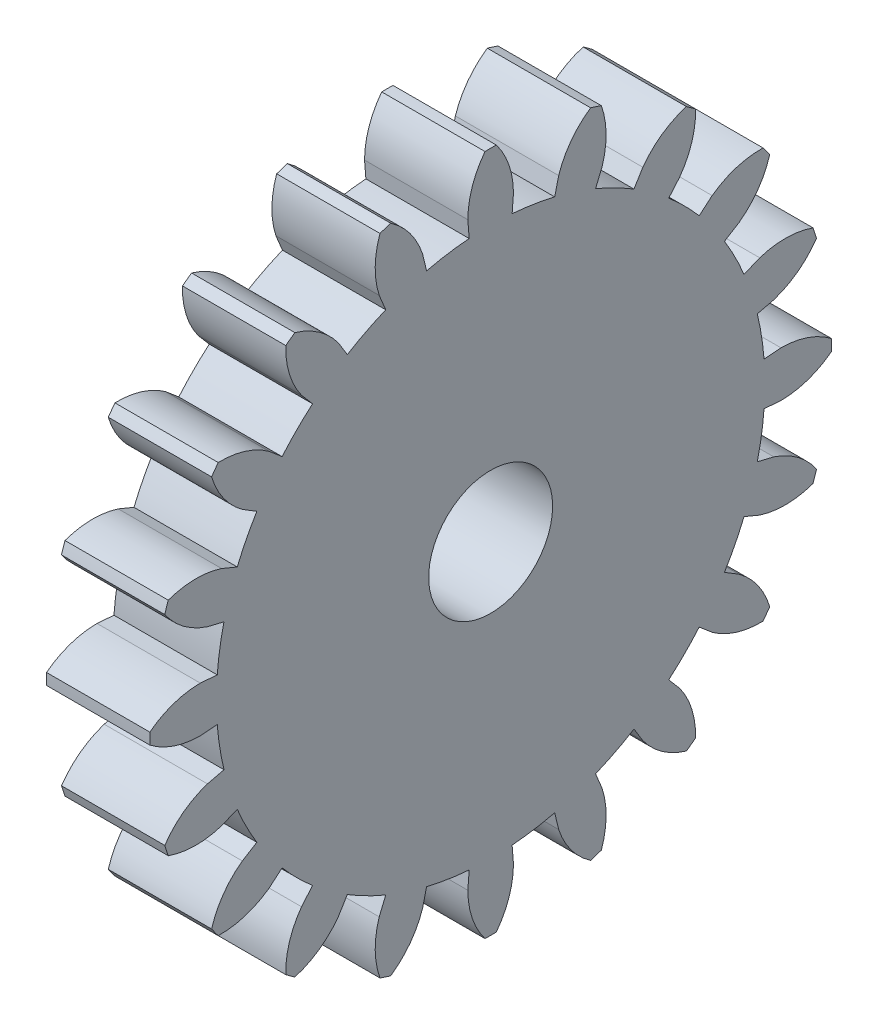
SolidWorks part; units mm, degrees
ref_plane "Front Plane" through (0, 0, 0) normal (1, 0, 0) x (0, 1, 0)
ref_plane "Top Plane" through (0, 0, 0) normal (0, 0, 1) x (0, 1, 0)
ref_plane "Right Plane" through (0, 0, 0) normal (0, 1, 0) x (-1, 0, 0)
sketch "Model" plane through (0, 0, 0) normal (1, 0, 0) x (0, 1, 0)
  line L0 (13.2342, -1.0397) -> (14.054, -1.1041)
  line L1 (14.054, 1.1041) -> (13.2342, 1.0397)
  line L2 (12.9078, 3.1007) -> (13.7073, 3.2929)
  line L3 (13.025, 5.3931) -> (12.2652, 5.0783)
  line L4 (11.3178, 6.9378) -> (12.0189, 7.3676)
  line L5 (10.7209, 9.1541) -> (10.0957, 8.6199)
  line L6 (8.6202, 10.0955) -> (9.1539, 10.7211)
  line L7 (7.3674, 12.0191) -> (6.9379, 11.3177)
  line L8 (5.0784, 12.2652) -> (5.3931, 13.0252)
  line L9 (3.293, 13.7076) -> (3.1008, 12.9078)
  line L10 (1.0397, 13.2342) -> (1.1041, 14.0542)
  line L11 (-1.1041, 14.0542) -> (-1.0397, 13.2342)
  line L12 (-3.1008, 12.9078) -> (-3.2929, 13.7076)
  line L13 (-5.3931, 13.0252) -> (-5.0784, 12.2652)
  line L14 (-6.9379, 11.3177) -> (-7.3679, 12.0191)
  line L15 (-9.1544, 10.7211) -> (-8.6202, 10.0955)
  line L16 (-10.0957, 8.6199) -> (-10.7214, 9.1541)
  line L17 (-12.0194, 7.3676) -> (-11.3178, 6.9378)
  line L18 (-12.2652, 5.0783) -> (-13.0255, 5.3931)
  line L19 (-13.7079, 3.2929) -> (-12.9078, 3.1007)
  line L20 (-13.2342, 1.0397) -> (-14.0545, 1.1041)
  line L21 (-14.0545, -1.1041) -> (-13.2342, -1.0397)
  line L22 (-12.9078, -3.1007) -> (-13.7079, -3.293)
  line L23 (-13.0255, -5.3931) -> (-12.2652, -5.0783)
  line L24 (-11.3178, -6.9378) -> (-12.0194, -7.3677)
  line L25 (-10.7214, -9.1542) -> (-10.0957, -8.6199)
  line L26 (-8.6202, -10.0955) -> (-9.1544, -10.7212)
  line L27 (-7.3679, -12.0191) -> (-6.9379, -11.3177)
  line L28 (-5.0784, -12.2652) -> (-5.3931, -13.0252)
  line L29 (-3.2929, -13.7076) -> (-3.1008, -12.9078)
  line L30 (-1.0397, -13.2342) -> (-1.1041, -14.0543)
  line L31 (1.1041, -14.0543) -> (1.0397, -13.2342)
  line L32 (3.1008, -12.9078) -> (3.293, -13.7076)
  line L33 (5.3931, -13.0252) -> (5.0784, -12.2652)
  line L34 (6.9379, -11.3177) -> (7.3674, -12.0191)
  line L35 (9.1539, -10.7212) -> (8.6202, -10.0955)
  line L36 (10.0957, -8.6199) -> (10.7209, -9.1542)
  line L37 (12.0189, -7.3677) -> (11.3178, -6.9378)
  line L38 (12.2652, -5.0783) -> (13.025, -5.3931)
  line L39 (13.7073, -3.293) -> (12.9078, -3.1007)
  circle A0 centre (0, 0) radius 3
  arc A1 (14.054, -1.1041) -> (16.4976, -0.2728) centre (14.0511, 2.9117) ccw
  arc A2 (16.4976, -0.2728) -> (16.4976, 0.2728) centre (0.0002, 0) ccw
  arc A3 (16.4976, 0.2728) -> (14.054, 1.1041) centre (14.0511, -2.9118) ccw
  arc A4 (13.2342, 1.0397) -> (12.9078, 3.1007) centre (0, 0) ccw
  arc A5 (13.7073, 3.2929) -> (15.7744, 4.8386) centre (12.4635, 7.1113) ccw
  arc A6 (15.7744, 4.8386) -> (15.6057, 5.3576) centre (0.0002, 0) ccw
  arc A7 (15.6057, 5.3576) -> (13.025, 5.3931) centre (14.2631, 1.5728) ccw
  arc A8 (12.2652, 5.0783) -> (11.3178, 6.9378) centre (0, 0) ccw
  arc A9 (12.0189, 7.3676) -> (13.5072, 9.4764) centre (9.656, 10.6148) ccw
  arc A10 (13.5072, 9.4764) -> (13.1865, 9.9179) centre (0.0002, 0.0026) ccw
  arc A11 (13.1865, 9.9179) -> (10.7209, 9.1541) centre (13.079, 5.9035) ccw
  arc A12 (10.0957, 8.6199) -> (8.6202, 10.0955) centre (0, 0) ccw
  arc A13 (9.1539, 10.7211) -> (9.9177, 13.1867) centre (5.9032, 13.0792) ccw
  arc A14 (9.9177, 13.1867) -> (9.4761, 13.5074) centre (0.002, 0.0005) ccw
  arc A15 (9.4761, 13.5074) -> (7.3674, 12.0191) centre (10.6146, 9.6562) ccw
  arc A16 (6.9379, 11.3177) -> (5.0784, 12.2652) centre (0, 0) ccw
  arc A17 (5.3931, 13.0252) -> (5.3577, 15.606) centre (1.5729, 14.2634) ccw
  arc A18 (5.3577, 15.606) -> (4.8386, 15.7747) centre (0, 0.0005) ccw
  arc A19 (4.8386, 15.7747) -> (3.293, 13.7076) centre (7.1114, 12.4638) ccw
  arc A20 (3.1008, 12.9078) -> (1.0397, 13.2342) centre (0, 0) ccw
  arc A21 (1.1041, 14.0542) -> (0.2728, 16.4979) centre (-2.9118, 14.0513) ccw
  arc A22 (0.2728, 16.4979) -> (-0.2728, 16.4979) centre (0, 0.0005) ccw
  arc A23 (-0.2728, 16.4979) -> (-1.1041, 14.0542) centre (2.9118, 14.0513) ccw
  arc A24 (-1.0397, 13.2342) -> (-3.1008, 12.9078) centre (0, 0) ccw
  arc A25 (-3.2929, 13.7076) -> (-4.8385, 15.7747) centre (-7.1113, 12.4638) ccw
  arc A26 (-4.8385, 15.7747) -> (-5.3576, 15.606) centre (0, 0.0005) ccw
  arc A27 (-5.3576, 15.606) -> (-5.3931, 13.0252) centre (-1.5728, 14.2634) ccw
  arc A28 (-5.0784, 12.2652) -> (-6.9379, 11.3177) centre (0, 0) ccw
  arc A29 (-7.3679, 12.0191) -> (-9.4768, 13.5074) centre (-10.6151, 9.6562) ccw
  arc A30 (-9.4768, 13.5074) -> (-9.9182, 13.1867) centre (0.0002, 0.0005) ccw
  arc A31 (-9.9182, 13.1867) -> (-9.1544, 10.7211) centre (-5.9038, 13.0792) ccw
  arc A32 (-8.6202, 10.0955) -> (-10.0957, 8.6199) centre (0, 0) ccw
  arc A33 (-10.7214, 9.1541) -> (-13.1869, 9.9179) centre (-13.0795, 5.9035) ccw
  arc A34 (-13.1869, 9.9179) -> (-13.5077, 9.4764) centre (-0.0007, -0.0006) ccw
  arc A35 (-13.5077, 9.4764) -> (-12.0194, 7.3676) centre (-9.6565, 10.6148) ccw
  arc A36 (-11.3178, 6.9378) -> (-12.2652, 5.0783) centre (0, 0) ccw
  arc A37 (-13.0255, 5.3931) -> (-15.6063, 5.3576) centre (-14.2636, 1.5728) ccw
  arc A38 (-15.6063, 5.3576) -> (-15.7749, 4.8386) centre (-0.0007, 0) ccw
  arc A39 (-15.7749, 4.8386) -> (-13.7079, 3.2929) centre (-12.4641, 7.1113) ccw
  arc A40 (-12.9078, 3.1007) -> (-13.2342, 1.0397) centre (0, 0) ccw
  arc A41 (-14.0545, 1.1041) -> (-16.4981, 0.2728) centre (-14.0516, -2.9118) ccw
  arc A42 (-16.4981, 0.2728) -> (-16.4981, -0.2728) centre (-0.0007, 0) ccw
  arc A43 (-16.4981, -0.2728) -> (-14.0545, -1.1041) centre (-14.0516, 2.9117) ccw
  arc A44 (-13.2342, -1.0397) -> (-12.9078, -3.1007) centre (0, 0) ccw
  arc A45 (-13.7079, -3.293) -> (-15.7749, -4.8386) centre (-12.4641, -7.1114) ccw
  arc A46 (-15.7749, -4.8386) -> (-15.6063, -5.3577) centre (-0.0007, 0) ccw
  arc A47 (-15.6063, -5.3577) -> (-13.0255, -5.3931) centre (-14.2636, -1.5729) ccw
  arc A48 (-12.2652, -5.0783) -> (-11.3178, -6.9378) centre (0, 0) ccw
  arc A49 (-12.0194, -7.3677) -> (-13.5077, -9.4765) centre (-9.6565, -10.6148) ccw
  arc A50 (-13.5077, -9.4765) -> (-13.1869, -9.918) centre (-0.0007, 0.0006) ccw
  arc A51 (-13.1869, -9.918) -> (-10.7214, -9.1542) centre (-13.0795, -5.9035) ccw
  arc A52 (-10.0957, -8.6199) -> (-8.6202, -10.0955) centre (0, 0) ccw
  arc A53 (-9.1544, -10.7212) -> (-9.9182, -13.1867) centre (-5.9038, -13.0793) ccw
  arc A54 (-9.9182, -13.1867) -> (-9.4768, -13.5075) centre (0.0002, -0.0005) ccw
  arc A55 (-9.4768, -13.5075) -> (-7.3679, -12.0191) centre (-10.6151, -9.6563) ccw
  arc A56 (-6.9379, -11.3177) -> (-5.0784, -12.2652) centre (0, 0) ccw
  arc A57 (-5.3931, -13.0252) -> (-5.3576, -15.606) centre (-1.5728, -14.2634) ccw
  arc A58 (-5.3576, -15.606) -> (-4.8385, -15.7747) centre (0, -0.0005) ccw
  arc A59 (-4.8385, -15.7747) -> (-3.2929, -13.7076) centre (-7.1113, -12.4638) ccw
  arc A60 (-3.1008, -12.9078) -> (-1.0397, -13.2342) centre (0, 0) ccw
  arc A61 (-1.1041, -14.0543) -> (-0.2728, -16.4979) centre (2.9118, -14.0513) ccw
  arc A62 (-0.2728, -16.4979) -> (0.2728, -16.4979) centre (0, -0.0005) ccw
  arc A63 (0.2728, -16.4979) -> (1.1041, -14.0543) centre (-2.9118, -14.0513) ccw
  arc A64 (1.0397, -13.2342) -> (3.1008, -12.9078) centre (0, 0) ccw
  arc A65 (3.293, -13.7076) -> (4.8386, -15.7747) centre (7.1114, -12.4638) ccw
  arc A66 (4.8386, -15.7747) -> (5.3577, -15.606) centre (0, -0.0005) ccw
  arc A67 (5.3577, -15.606) -> (5.3931, -13.0252) centre (1.5729, -14.2634) ccw
  arc A68 (5.0784, -12.2652) -> (6.9379, -11.3177) centre (0, 0) ccw
  arc A69 (7.3674, -12.0191) -> (9.4761, -13.5075) centre (10.6146, -9.6563) ccw
  arc A70 (9.4761, -13.5075) -> (9.9177, -13.1867) centre (0.002, -0.0005) ccw
  arc A71 (9.9177, -13.1867) -> (9.1539, -10.7212) centre (5.9032, -13.0793) ccw
  arc A72 (8.6202, -10.0955) -> (10.0957, -8.6199) centre (0, 0) ccw
  arc A73 (10.7209, -9.1542) -> (13.1865, -9.918) centre (13.079, -5.9035) ccw
  arc A74 (13.1865, -9.918) -> (13.5072, -9.4765) centre (0.0002, -0.0026) ccw
  arc A75 (13.5072, -9.4765) -> (12.0189, -7.3677) centre (9.656, -10.6148) ccw
  arc A76 (11.3178, -6.9378) -> (12.2652, -5.0783) centre (0, 0) ccw
  arc A77 (13.025, -5.3931) -> (15.6057, -5.3577) centre (14.2631, -1.5729) ccw
  arc A78 (15.6057, -5.3577) -> (15.7744, -4.8386) centre (0.0002, 0) ccw
  arc A79 (15.7744, -4.8386) -> (13.7073, -3.293) centre (12.4635, -7.1114) ccw
  arc A80 (12.9078, -3.1007) -> (13.2342, -1.0397) centre (0, 0) ccw
  text T0 "Driver Gear (M1.5 N20 D30 PA20DEG)" font "SWTXT" height 2.25
  point P203 (-11.8281, 6.0267)
  dimension "D2" = 6
  dimension "D3" = 16.4984
  dimension "D4" = 8.988
  dimension "D5" = 3.1454
  dimension "D1" = 13.275
extrude "Boss-Extrude3" add sketch "Model" along normal blind 5 contours L0 A1 A2 A3 L1 A4 L2 A5 A6 A7 L3 A8 L4 A9 A10 A11 L5 A12 L6 A13 A14 A15 L7 A16 L8 A17 A18 A19 L9 A20 L10 A21 A22 A23 L11 A24 L12 A25 A26 A27 L13 A28 L14 A29 A30 A31 L15 A32 L16 A33 A34 A35 L17 A36 L18 A37 A38 A39 L19 A40 L20 A41 A42 A43 L21 A44 L22 A45 A46 A47 L23 A48 L24 A49 A50 A51 L25 A52 L26 A53 A54 A55 L27 A56 L28 A57 A58 A59 L29 A60 L30 A61 A62 A63 L31 A64 L32 A65 A66 A67 L33 A68 L34 A69 A70 A71 L35 A72 L36 A73 A74 A75 L37 A76 L38 A77 A78 A79 L39 A80 | A0
